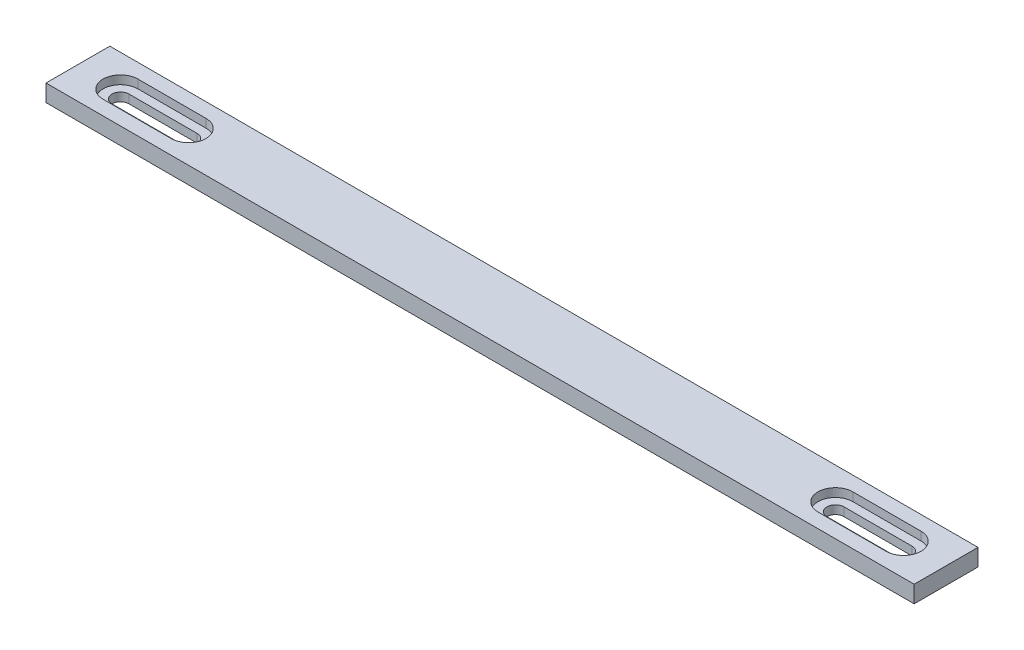
SolidWorks part; units mm, degrees
material "PMMA"
ref_plane "前视基准面" through (0, 0, 0) normal (0, 0, 1) x (1, 0, 0)
ref_plane "上视基准面" through (0, 0, 0) normal (0, 1, 0) x (1, 0, 0)
ref_plane "右视基准面" through (0, 0, 0) normal (1, 0, 0) x (0, 0, -1)
sketch "Sketch1" plane through (0, 0, 0) normal (1, 0, 0) x (0, 0, -1)
  line L0 (0, 0) -> (0, -4)
  line L1 (0, -4) -> (15, -4)
  line L2 (15, -4) -> (15, 0)
  line L3 (15, 0) -> (0, 0)
  dimension "D1" = 15
  dimension "D2" = 4
extrude "Boss-Extrude1" add sketch "Sketch1" along normal blind 204
sketch "Sketch3" plane through (0, 0, 0) normal (0, 1, 0) x (1, 0, 0)
  line L0 (-10.3442, 7.5) -> (315.3615, 7.5) construction
  line L1 (204, 15) -> (0, 15) construction
  line L2 (178, 7.5) -> (194, 7.5) construction
  line L3 (10, 7.5) -> (26, 7.5) construction
  line L4 (10, 9.5) -> (26, 9.5)
  line L5 (10, 5.5) -> (26, 5.5)
  line L6 (0, 15) -> (0, 0) construction
  line L7 (178, 9.5) -> (194, 9.5)
  line L8 (178, 5.5) -> (194, 5.5)
  arc A1 (10, 9.5) -> (10, 5.5) centre (10, 7.5) ccw
  arc A2 (26, 5.5) -> (26, 9.5) centre (26, 7.5) ccw
  arc A3 (178, 9.5) -> (178, 5.5) centre (178, 7.5) ccw
  arc A4 (194, 5.5) -> (194, 9.5) centre (194, 7.5) ccw
  point P6 (18, 7.5)
  point P17 (186, 7.5)
  dimension "D2" = 2
  dimension "D1" = 7.5
  dimension "D3" = 10
  dimension "D4" = 16
  dimension "D6" = 184
  dimension "D5" = 2
extrude "Cut-Extrude1" cut sketch "Sketch3" against normal through all
sketch "Sketch4" plane through (0, 0, 0) normal (0, 1, 0) x (1, 0, 0)
  line L0 (10, 7.5) -> (26, 7.5) construction
  line L1 (10, 11.6) -> (26, 11.6)
  line L2 (10, 3.4) -> (26, 3.4)
  line L3 (178, 7.5) -> (194, 7.5) construction
  line L4 (178, 11.6) -> (194, 11.6)
  line L5 (178, 3.4) -> (194, 3.4)
  arc A0 (10, 11.6) -> (10, 3.4) centre (10, 7.5) ccw
  arc A1 (26, 3.4) -> (26, 11.6) centre (26, 7.5) ccw
  arc A2 (178, 11.6) -> (178, 3.4) centre (178, 7.5) ccw
  arc A3 (194, 3.4) -> (194, 11.6) centre (194, 7.5) ccw
  point P4 (18, 7.5)
  point P13 (186, 7.5)
  dimension "D1" = 4.1
  dimension "D3" = 168
  dimension "D2" = 2
extrude "Cut-Extrude2" cut sketch "Sketch4" against normal blind 2
